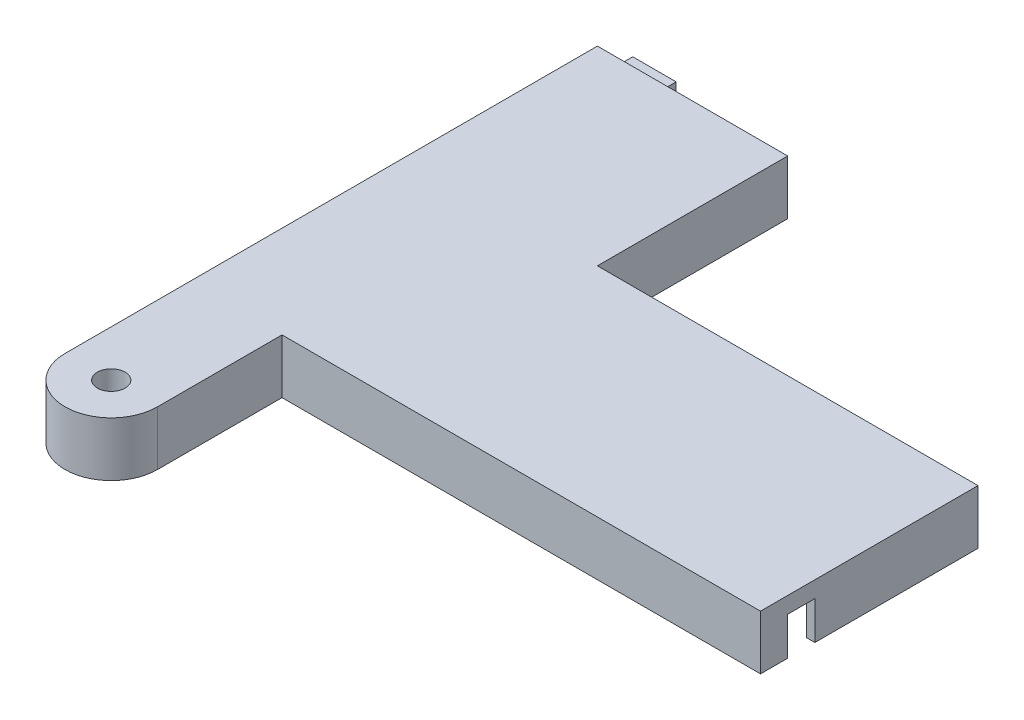
SolidWorks part; units mm, degrees
ref_plane "Front Plane" through (0, 0, 0) normal (0, 0, 1) x (1, 0, 0)
ref_plane "Top Plane" through (0, 0, 0) normal (0, 1, 0) x (1, 0, 0)
ref_plane "Right Plane" through (0, 0, 0) normal (1, 0, 0) x (0, 0, -1)
sketch "CornerrSketch1" plane through (0, 0, 0) normal (0, 1, 0) x (1, 0, 0)
  line L0 (0, 195.825) -> (70, 195.825)
  line L5 (70, 195.825) -> (70, 125.825)
  line L6 (70, 125.825) -> (210, 125.825)
  line L7 (210, 45.825) -> (210, 125.825)
  line L11 (34, 0) -> (34, 45.825)
  line L12 (34, 45.825) -> (210, 45.825)
  line L13 (0, 195.825) -> (0, 0)
  arc A0 (0, 0) -> (34, 0) centre (17, 0) ccw
  point P2 (35, 195.825)
  dimension "D3" = 34
  dimension "D4" = 70
  dimension "D2" = 80
  dimension "D1" = 45.825
  dimension "D6" = 210
  dimension "D5" = 150
extrude "CornerBoss-Extrude1" add sketch "CornerrSketch1" along normal blind 20
shell "Shell4" thickness 3
sketch "PadSketch2" plane through (0, 17, 0) normal (0, -1, 0) x (1, 0, 0)
  circle A0 centre (17, 0) radius 12
  dimension "D1" = 24
extrude "PadBoss-Extrude2" add sketch "PadSketch2" along normal blind 10
sketch "StepperShaftHoleCutSketch3" plane through (0, 7, 0) normal (0, -1, 0) x (1, 0, 0)
  circle A0 centre (17, 0) radius 5.1
  dimension "D1" = 10.2
extrude "StepperShaftHoleCut-Extrude1" cut sketch "StepperShaftHoleCutSketch3" against normal through all
sketch "ThreadedNutMountHolesSketch4" plane through (0, 7, 0) normal (0, -1, 0) x (-1, 0, 0)
  circle A8 centre (-17, 8) radius 2
  circle A9 centre (-17, -8) radius 2
  circle A10 centre (-25, 0) radius 2
  circle A11 centre (-9, 0) radius 2
  dimension "D1" = 4
  dimension "D3" = 16
  dimension "D4" = 8
  dimension "D5" = 16
extrude "ThreadedNutMountHolesCut-Extrude2" cut sketch "ThreadedNutMountHolesSketch4" against normal blind 10
sketch "BRPegHoleSketch1" plane through (210, 0, 0) normal (1, 0, 0) x (0, 0, -1)
  line L1 (55.825, 14) -> (65.825, 14)
  line L2 (55.825, 14) -> (55.825, 0)
  line L3 (55.825, 0) -> (65.825, 0)
  line L4 (65.825, 14) -> (65.825, 0)
  line L6 (45.825, 0) -> (125.825, 0) construction
  line L7 (45.825, 20) -> (45.825, 0) construction
  dimension "D2" = 10
  dimension "D3" = 14
  dimension "D1" = 10
extrude "BRPegHoleCut-Extrude1" cut sketch "BRPegHoleSketch1" against normal blind 3
sketch "TopPegSketch2" plane through (0, 0, -195.825) normal (0, 0, -1) x (-1, 0, 0)
  line L0 (0, 20) -> (0, 0) construction
  line L1 (-19.9, 13.9) -> (-10.1, 13.9)
  line L2 (-19.9, 13.9) -> (-19.9, 0)
  line L3 (-19.9, 0) -> (-10.1, 0)
  line L4 (-10.1, 13.9) -> (-10.1, 0)
  line L6 (-70, 0) -> (0, 0) construction
  dimension "D2" = 13.9
  dimension "D3" = 9.8
  dimension "D1" = 10.1
extrude "TopPegBoss-Extrude1" add sketch "TopPegSketch2" along normal blind 3
sketch "TopPegCapSketch3" plane through (0, 0, -198.825) normal (0, 0, -1) x (-1, 0, 0)
  line L1 (-22.9, 17) -> (-6.9, 17)
  line L2 (-22.9, 17) -> (-22.9, 0)
  line L3 (-22.9, 0) -> (-6.9, 0)
  line L4 (-6.9, 17) -> (-6.9, 0)
  line L5 (-19.9, 0) -> (-10.1, 0) construction
  line L7 (-19.9, 13.9) -> (-19.9, 0) construction
  dimension "D1" = 16
  dimension "D3" = 17
  dimension "D2" = 3
extrude "TopPegCapBoss-Extrude2" add sketch "TopPegCapSketch3" along normal blind 3.1
sketch "CenterPegHoleCutSketch1" plane through (0, 0, -125.825) normal (0, 0, -1) x (-1, 0, 0)
  line L0 (-210, 0) -> (-70, 0) construction
  line L1 (-180, 14) -> (-170, 14)
  line L2 (-180, 14) -> (-180, 0)
  line L3 (-180, 0) -> (-170, 0)
  line L4 (-170, 14) -> (-170, 0)
  line L6 (-70, 20) -> (-70, 0) construction
  dimension "D2" = 10
  dimension "D1" = 14
  dimension "D3" = 100
extrude "CenterPegHoleCut-Extrude1" cut sketch "CenterPegHoleCutSketch1" against normal blind 3
equation "\"RailThickness\"= .125in'Spec"
equation "\"StepperMountingHoleDistance\"= 31mm'Spec"
equation "\"StepperMountingHoleOffsetFromLeftOrRightSide\"= \"StepperMountingHoleOffsetFromItsSide\" + \"RailThickness\""
equation "\"StepperMountingHoleOffsetFromItsSide\"= 5.5mm'Spec"
equation "\"FrontBackRailLength\"= 510mm"
equation "\"DistanceBetweenLeftToRightStepperHoles\"= \"FrontBackRailLength\" - \"StepperMountingHoleOffsetFromLeftOrRightSide\" * 2 - \"StepperMountingHoleDistance\"'Equals 461.65"
equation "\"BedThickness\"= 20mm"
equation "\"BedLLongSide\"= \"BedThirdSize\" * 3'Equals 210"
equation "\"BedLShortSide\"= \"BedThirdSize\" * 2'Equals 140"
equation "\"BedLWidth\"= \"BedThirdSize\"'Equals 70"
equation "\"D4@CornerrSketch1\"=\"BedLWidth\" + \"BedIncreasedByLength\"/2"
equation "\"BedIncreasedByWidth\"= 20mm"
equation "\"BedIncreasedByLength\"= 0mm"
equation "\"BedThirdSize\"= 70mm"
equation "\"BedWidth\"= \"BedInnerSquareWidth\" + \"BedLWidth\" * 2 + \"BedIncreasedByWidth\"'Equals 370"
equation "\"BedInnerSquareWidth\"= \"BedThirdSize\" * 3'Equals 210"
equation "\"StandardWallThickness\"= 3mm"
equation "\"D2@BRPegHoleSketch1\"=\"BedPegHoleWidth\""
equation "\"D1@BRPegHoleSketch1\"=\"BedTopPegOffsetFromSide\" "
equation "\"D3@BRPegHoleSketch1\"=\"BedPegHoleHeight\""
equation "\"D1@BRPegHoleCut-Extrude1\" = \"StandardWallThickness\""
equation "\"D2@TopPegSketch2\"=\"BedPegHeight\""
equation "\"D1@TopPegBoss-Extrude1\" = \"StandardWallThickness\""
equation "\"D3@TopPegCapSketch3\"=\"BedPegCapHeight\""
equation "\"D1@TopPegCapSketch3\"=\"BedPegCapWidth\""
equation "\"D1@TopPegCapBoss-Extrude2\"=\"BedPegBoss\""
equation "\"D2@TopPegCapSketch3\"=\"StandardWallThickness\""
equation "\"DistanceFromBedSideToStepperHole\"= ( \"DistanceBetweenLeftToRightStepperHoles\" - \"BedWidth\" ) / 2'Equals 45.825"
equation "\"DistanceFromBedFrontToFirstLeftStepperHole\"= \"LeadScrewNutPadSize\" + 10mm'Equals 34"
equation "\"D3@CornerrSketch1\"=\"DistanceFromBedFrontToFirstLeftStepperHole\""
equation "\"LeadScrewNutPadSize\"= \"LeadScrewNutMountingHoleFlangeDiameter\" + 2mm'Equals 24"
equation "\"D1@PadSketch2\" = \"LeadScrewNutPadSize\""
equation "\"D1@StepperShaftHoleCutSketch3\"=\"LeadScrewNutInnerShaftFlangeDiameter\""
equation "\"D2@CornerrSketch1\"=\"BedLWidth\" + \"BedIncreasedByWidth\"/2"
equation "\"D6@CornerrSketch1\"=\"BedLLongSide\""
equation "\"D1@TopPegSketch2\"=\"BedTopPegOffsetFromSide\" + .1mm"
equation "\"D1@CornerrSketch1\"=\"DistanceFromBedSideToStepperHole\""
equation "\"D5@CornerrSketch1\"=\"BedLShortSide\" + \"BedIncreasedByWidth\"/2"
equation "\"LeadScrewNutInnerShaftFlangeDiameter\"= 10.2mm'Spec"
equation "\"LeadScrewNutMountHoleDiameter\" = \"M3HeatInsertHoleDiameter\"'Spec is 4.1 but smaller for tapping"
equation "\"LeadScrewNutMountingHoleFlangeDiameter\"= 22mm'Spec"
equation "\"LeadScrewNutMountingHoleDistance\"= 16mm'Spec"
equation "\"D1@ThreadedNutMountHolesSketch4\"=\"LeadScrewNutMountHoleDiameter\""
equation "\"D2@ThreadedNutMountHolesSketch4\"=\"LeadScrewNutMountingHoleDistance\"/2"
equation "\"D3@ThreadedNutMountHolesSketch4\"=\"LeadScrewNutMountingHoleDistance\""
equation "\"D4@ThreadedNutMountHolesSketch4\"=\"LeadScrewNutMountingHoleDistance\"/2"
equation "\"D5@ThreadedNutMountHolesSketch4\"=\"LeadScrewNutMountingHoleDistance\""
equation "\"LeadScrewNutPadDepth\"= \"BedThickness\" / 2'Equals 10"
equation "\"D1@PadBoss-Extrude2\"=\"LeadScrewNutPadDepth\""
equation "\"D1@ThreadedNutMountHolesCut-Extrude2\"= \"LeadScrewNutPadDepth\""
equation "\"BedPegHoleWidth\"= 10mm"
equation "\"BedPegHoleHeight\"= \"BedThickness\" - \"StandardWallThickness\" * 2'Equals 14"
equation "\"BedPegWidth\"= \"BedPegHoleWidth\" - .1mm * 2'For easier assembly"
equation "\"BedPegHeight\"= \"BedPegHoleHeight\" - .1mm'For easier assembly"
equation "\"BedTopPegOffsetFromSide\"= 10mm"
equation "\"BedPegBoss\"= \"StandardWallThickness\" + .1mm'For easier assembly"
equation "\"BedPegCapHeight\"= \"BedThickness\" - \"StandardWallThickness\"'Equals 17"
equation "\"BedPegCapWidth\"= \"BedThickness\" / 2 + \"StandardWallThickness\" * 2'Equals 16"
equation "\"D3@TopPegSketch2\"=\"BedPegWidth\""
equation "\"D1@CenterPegHoleCutSketch1\" = \"BedPegHoleHeight\""
equation "\"D2@CenterPegHoleCutSketch1\" = \"BedPegHoleWidth\""
equation "\"D3@CenterPegHoleCutSketch1\"= \"BedInnerSquareWidth\" / 2 - \"BedPegHoleWidth\" / 2"
equation "\"D1@CenterPegHoleCut-Extrude1\"=\"StandardWallThickness\""
equation "\"M3HeatInsertHoleDiameter\"= 4mm"
